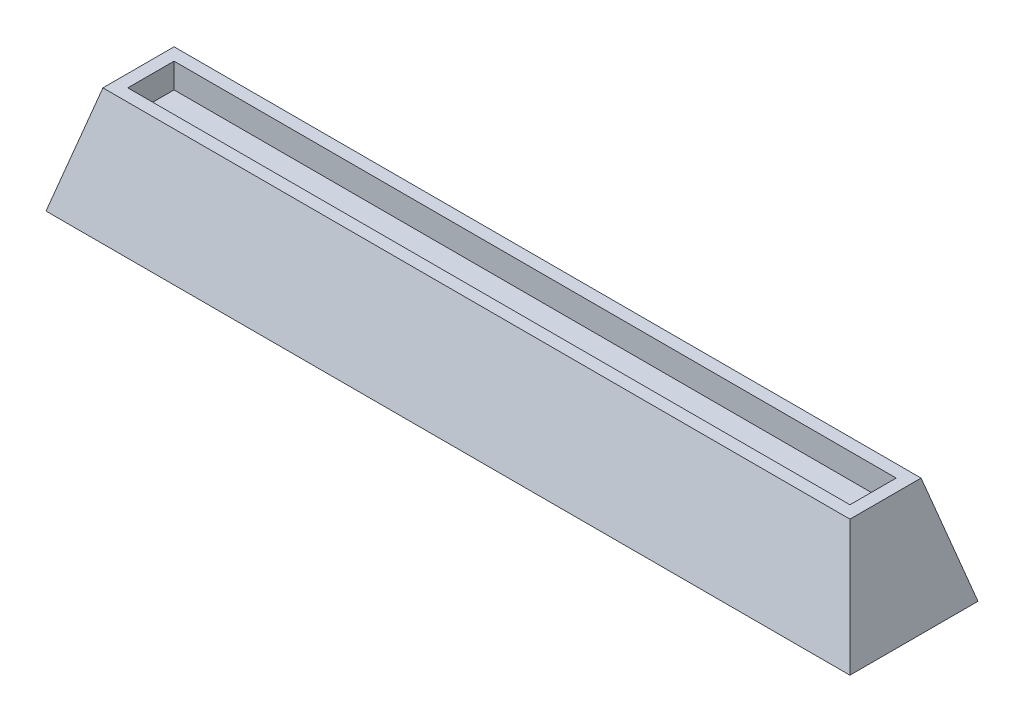
SolidWorks part; units mm, degrees
ref_plane "前视基准面" through (0, 0, 0) normal (0, 0, 1) x (1, 0, 0)
ref_plane "上视基准面" through (0, 0, 0) normal (0, 1, 0) x (1, 0, 0)
ref_plane "右视基准面" through (0, 0, 0) normal (1, 0, 0) x (0, 0, -1)
sketch "草图1" plane through (0, 0, 0) normal (0, 1, 0) x (1, 0, 0)
  line L1 (-54.3399, 13.9343) -> (46.6601, 13.9343) construction
  line L2 (-54.3399, 13.9343) -> (-54.3399, 7.9343) construction
  line L3 (-54.3399, 7.9343) -> (46.6601, 7.9343) construction
  line L4 (46.6601, 13.9343) -> (46.6601, 7.9343) construction
  line L5 (-56.3399, 15.9343) -> (48.6601, 15.9343)
  line L6 (-56.3399, 15.9343) -> (-56.3399, 5.9343)
  line L7 (-56.3399, 5.9343) -> (48.6601, 5.9343)
  line L8 (48.6601, 15.9343) -> (48.6601, 5.9343)
  point P8 (0, 0)
  dimension "D1" = 101
  dimension "D2" = 6
  dimension "D3" = 2
  dimension "D4" = 2
  dimension "D5" = 2
  dimension "D6" = 2
ref_plane "基准面1" through (0, -15, 0) normal (0, 1, 0) x (1, 0, 0)
sketch "草图2" plane through (0, -15, 0) normal (0, 1, 0) x (1, 0, 0)
  line L0 (-56.3399, 15.9343) -> (-56.3399, 5.9343) construction
  line L1 (-60.3399, 19.9343) -> (52.6601, 19.9343)
  line L2 (-60.3399, 19.9343) -> (-60.3399, 1.9343)
  line L3 (-60.3399, 1.9343) -> (52.6601, 1.9343)
  line L4 (52.6601, 19.9343) -> (52.6601, 1.9343)
  line L5 (48.6601, 15.9343) -> (48.6601, 5.9343) construction
  line L6 (-56.3399, 15.9343) -> (48.6601, 15.9343) construction
  line L7 (-56.3399, 5.9343) -> (48.6601, 5.9343) construction
  dimension "D1" = 4
  dimension "D2" = 4
  dimension "D3" = 4
  dimension "D4" = 4
loft "放样1" add profiles "草图2", "草图1"
sketch "草图3" plane through (0, 0, 0) normal (0, 1, 0) x (1, 0, 0)
  line L0 (48.6601, 15.9343) -> (-56.3399, 15.9343) construction
  line L1 (-54.5899, 14.1843) -> (46.9101, 14.1843)
  line L2 (-54.5899, 14.1843) -> (-54.5899, 7.6843)
  line L3 (-54.5899, 7.6843) -> (46.9101, 7.6843)
  line L4 (46.9101, 14.1843) -> (46.9101, 7.6843)
  line L5 (48.6601, 5.9343) -> (48.6601, 15.9343) construction
  point P5 (-3.8399, 14.1843)
  point P6 (-3.8399, 15.9343)
  point P7 (48.6601, 10.9343)
  point P10 (46.9101, 10.9343)
  point P13 (0, 0)
  point P14 (0, 0)
  dimension "D1" = 101.5
  dimension "D2" = 6.5
extrude "切除-拉伸1" cut sketch "草图3" against normal blind 3.5
sketch "草图4" plane through (0, 3.9671, -14.8765) normal (0, 0.2577, -0.9662) x (-1, 0, 0)
  line L0 (-48.6601, -4.1057) -> (56.3399, -4.1057) construction
  line L1 (-52.6601, -19.6299) -> (60.3399, -19.6299) construction
  line L2 (-50.6601, -15.4339) -> (58.3399, -15.4339) construction
  text T0 "中国业余无线电" font "微软雅黑" height in points 26
  point P1 (3.8399, -4.1057)
  point P2 (3.8399, -19.6299)
  point P8 (0, 0)
  point P9 (0, 0)
  point P13 (0, 0)
extrude "切除-拉伸2" cut sketch "草图4" against normal blind 1.5
